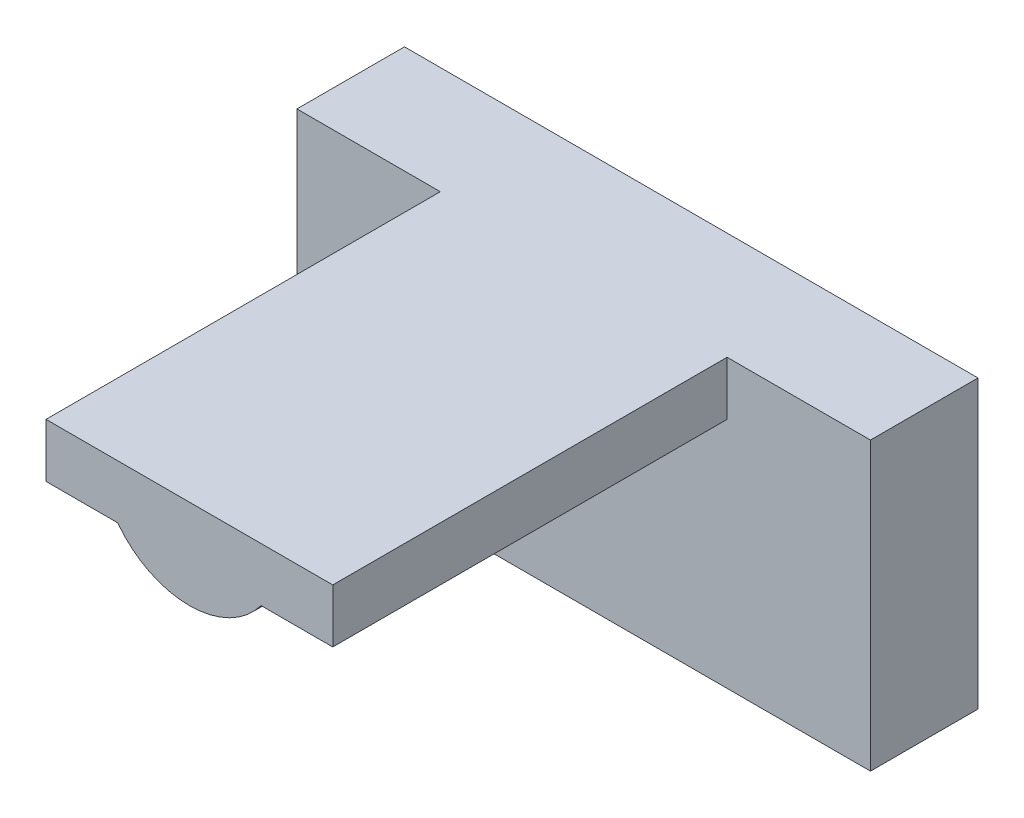
SolidWorks part; units mm, degrees
ref_plane "Front Plane" through (0, 0, 0) normal (0, 0, 1) x (1, 0, 0)
ref_plane "Top Plane" through (0, 0, 0) normal (0, 1, 0) x (1, 0, 0)
ref_plane "Right Plane" through (0, 0, 0) normal (1, 0, 0) x (0, 0, -1)
sketch "Sketch1" plane through (0, 0, 0) normal (0, 0, 1) x (1, 0, 0)
  line L1 (-21.5695, 14.0448) -> (-5.5695, 14.0448)
  line L2 (-21.5695, 14.0448) -> (-21.5695, 22.0448)
  line L3 (-21.5695, 22.0448) -> (-5.5695, 22.0448)
  line L4 (-5.5695, 14.0448) -> (-5.5695, 22.0448)
  line L5 (-21.5695, 14.0448) -> (-5.5695, 22.0448) construction
  line L6 (-21.5695, 22.0448) -> (-5.5695, 14.0448) construction
  dimension "D1" = 16
  dimension "D2" = 8
extrude "Boss-Extrude1" add sketch "Sketch1" along normal blind 3
shell "Shell3" thickness 1
sketch "Sketch2" plane through (0, 0, 2) normal (0, 0, -1) x (-1, 0, 0)
  line L0 (21.5695, 22.0448) -> (21.5695, 14.0448) construction
  line L1 (5.5695, 22.0448) -> (21.5695, 22.0448) construction
  circle A0 centre (13.5695, 18.0448) radius 1.5
  circle A1 centre (13.5695, 18.0448) radius 0.8
  point P4 (21.5695, 18.0448)
  point P7 (13.5695, 22.0448)
  dimension "D1" = 3
  dimension "D2" = 8
  dimension "D3" = 4
  dimension "D4" = 0.7
extrude "Boss-Extrude2" add sketch "Sketch2" along normal blind 2
sketch "Sketch3" plane through (0, 0, 3) normal (0, 0, 1) x (1, 0, 0)
  line L0 (-5.5695, 22.0448) -> (-21.5695, 22.0448) construction
  line L1 (-17.5695, 22.0448) -> (-9.5695, 22.0448)
  line L2 (-9.5695, 22.0448) -> (-9.5695, 20.5448)
  line L3 (-9.5695, 20.5448) -> (-11.5695, 20.5448)
  line L4 (-13.5695, 22.0448) -> (-13.5695, 14.0448) construction
  line L5 (-21.5695, 14.0448) -> (-5.5695, 14.0448) construction
  line L6 (-13.5695, 20.5448) -> (-13.6847, 20.5448)
  line L7 (-17.5695, 20.5448) -> (-15.5695, 20.5448)
  line L8 (-17.5695, 22.0448) -> (-17.5695, 20.5448)
  arc A0 (-15.5695, 20.5448) -> (-11.5695, 20.5448) centre (-13.5695, 22.0448) ccw
  dimension "D1" = 5
  dimension "D2" = 4
  dimension "D3" = 1.5
extrude "Boss-Extrude3" add sketch "Sketch3" along normal blind 11
